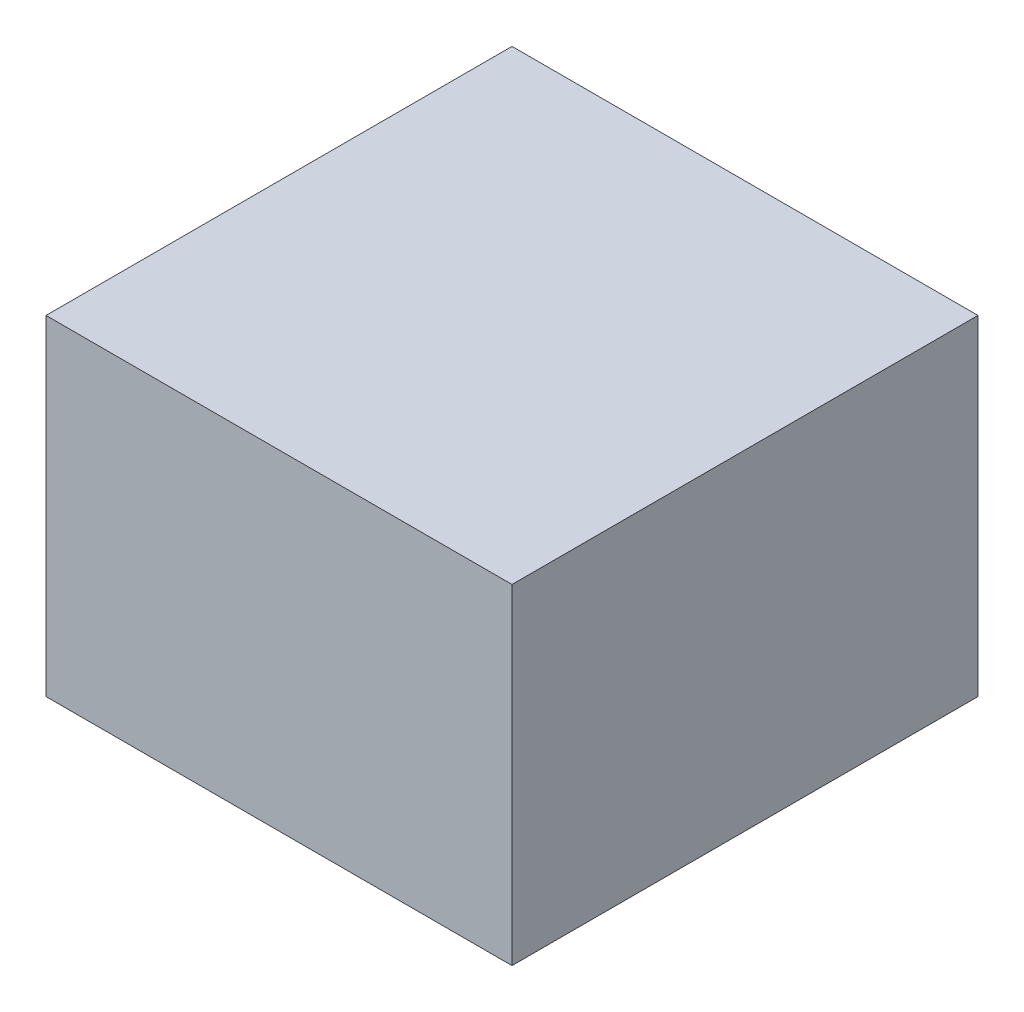
SolidWorks part; units mm, degrees
material "Custom Plastic"
ref_plane "X-Y Datum" through (0, 0, 0) normal (0, 0, 1) x (1, 0, 0)
ref_plane "X-Z Datum" through (0, 0, 0) normal (0, 1, 0) x (1, 0, 0)
ref_plane "Y-Z Datum" through (0, 0, 0) normal (1, 0, 0) x (0, 0, -1)
sketch "Sketch1" plane through (0, 0, 0) normal (0, 0, 1) x (1, 0, 0)
  line L1 (-30.48, -21.59) -> (30.48, -21.59)
  line L2 (-30.48, -21.59) -> (-30.48, 21.59)
  line L3 (-30.48, 21.59) -> (30.48, 21.59)
  line L4 (30.48, -21.59) -> (30.48, 21.59)
  line L5 (-30.48, -21.59) -> (30.48, 21.59) construction
  line L6 (-30.48, 21.59) -> (30.48, -21.59) construction
  point P0 (0, 0)
  dimension "D1" = 43.18
  dimension "D2" = 60.96
extrude "Boss-Extrude1" add sketch "Sketch1" along normal blind 60.96
